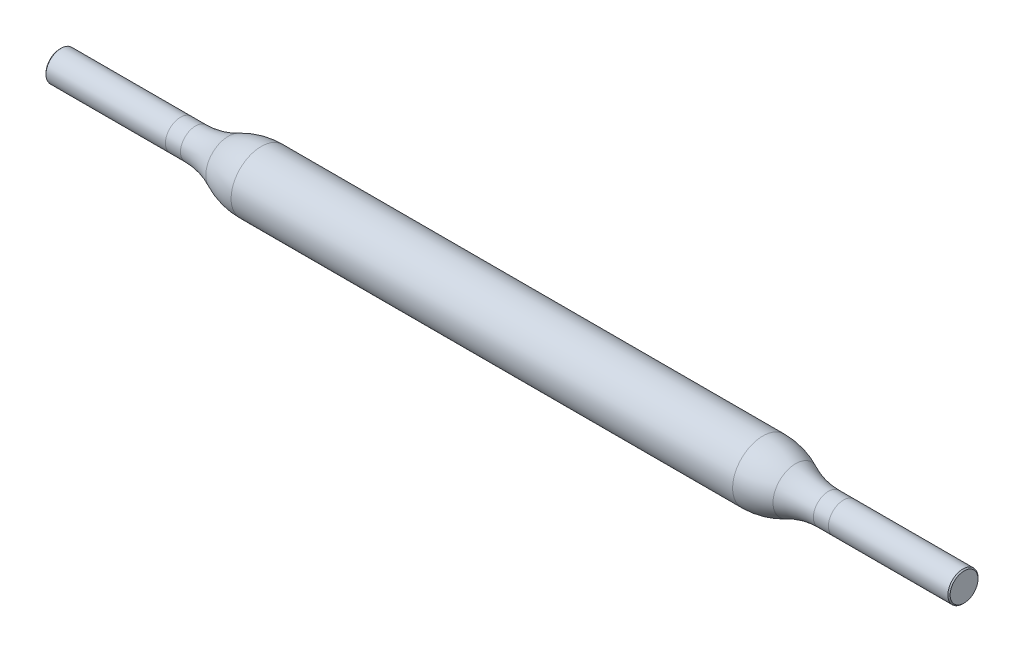
SolidWorks part; units mm, degrees
ref_plane "Front Plane" through (0, 0, 0) normal (0, 0, 1) x (1, 0, 0)
ref_plane "Top Plane" through (0, 0, 0) normal (0, 1, 0) x (1, 0, 0)
ref_plane "Right Plane" through (0, 0, 0) normal (1, 0, 0) x (0, 0, -1)
sketch "Sketch1" plane through (0, 0, 0) normal (0, 0, 1) x (1, 0, 0)
  line L0 (-30, 0) -> (30, 0)
  line L1 (30, 0) -> (30, 1)
  line L2 (-30, 0) -> (-30, 1)
  line L3 (-30, 1) -> (-21, 1)
  line L4 (30, 1) -> (21, 1)
  line L5 (-16.6411, 2) -> (16.6411, 2)
  arc A0 (-21, 1) -> (-18.8206, 1.5) centre (-21, 6) ccw
  arc A1 (18.8206, 1.5) -> (21, 1) centre (21, 6) ccw
  arc A2 (16.6411, 2) -> (18.8206, 1.5) centre (16.6411, -3) cw
  arc A3 (-16.6411, 2) -> (-18.8206, 1.5) centre (-16.6411, -3) ccw
  point P12 (18, 2)
  point P17 (-18, 2)
  dimension "D9" = 5
  dimension "D1" = 60
  dimension "D2" = 1
  dimension "D3" = 1
  dimension "D4" = 9
  dimension "D5" = 9
  dimension "D6" = 2
  dimension "D7" = 3
  dimension "D8" = 3
revolve "Revolve1" add sketch "Sketch1" angle 360 about L0
sketch "Sketch2" plane through (0, 0, 0) normal (0, 0, 1) x (1, 0, 0)
  line L0 (-22, 5.7136) -> (-22, -6.0269)
  line L1 (22, 5.7136) -> (22, -6.0269)
  line L2 (-30, 1) -> (-30, -1) construction
  line L3 (30, -1) -> (30, 1) construction
  dimension "D1" = 8
  dimension "D2" = 8
split line "Split Line1"
chamfer "Chamfer1" distance 0.075 angle 45 2 edges at (-30, -1, 0) (30, -1, 0)
